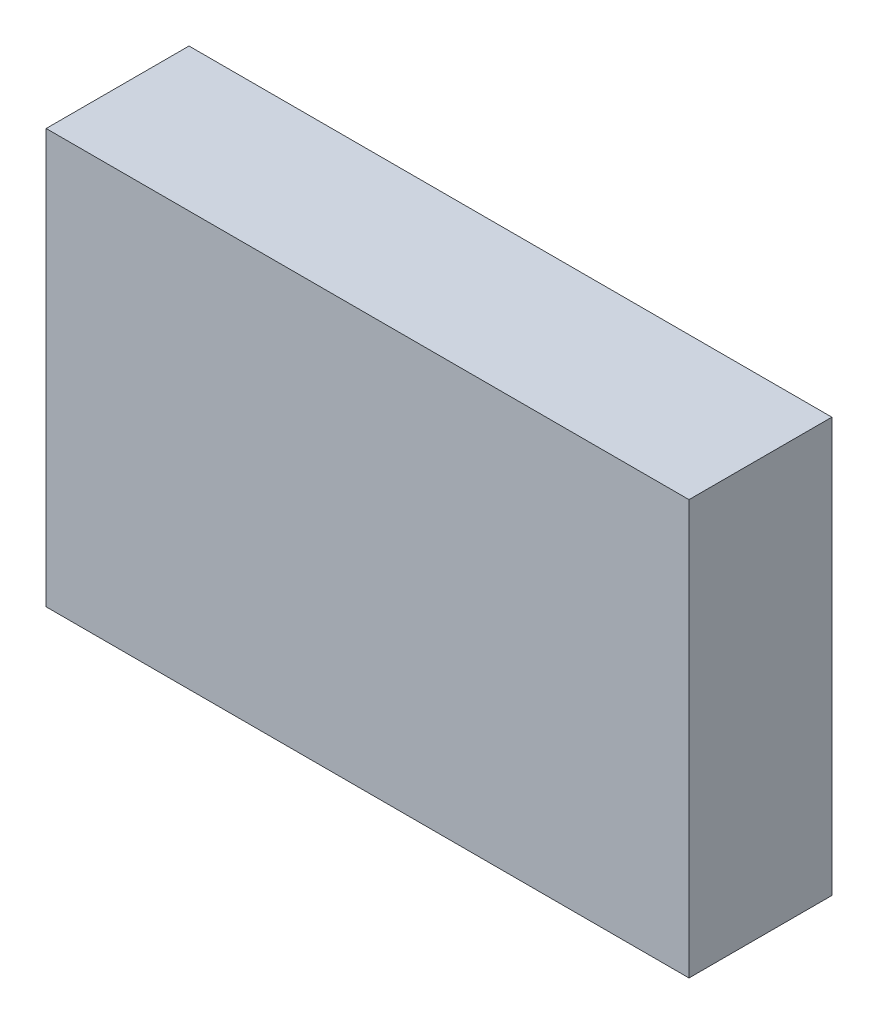
SolidWorks part; units mm, degrees
ref_plane "Front Plane" through (0, 0, 0) normal (0, 0, 1) x (1, 0, 0)
ref_plane "Top Plane" through (0, 0, 0) normal (0, 1, 0) x (1, 0, 0)
ref_plane "Right Plane" through (0, 0, 0) normal (1, 0, 0) x (0, 0, -1)
sketch "Sketch1" plane through (0, 0, 0) normal (0, 0, 1) x (1, 0, 0)
  line L1 (-22.5, 14.5) -> (22.5, 14.5)
  line L2 (-22.5, 14.5) -> (-22.5, -14.5)
  line L3 (-22.5, -14.5) -> (22.5, -14.5)
  line L4 (22.5, 14.5) -> (22.5, -14.5)
  line L5 (-22.5, 14.5) -> (22.5, -14.5) construction
  line L6 (-22.5, -14.5) -> (22.5, 14.5) construction
  point P0 (0, 0)
  dimension "D1" = 29
  dimension "D2" = 45
extrude "Boss-Extrude1" add sketch "Sketch1" along normal blind 10
